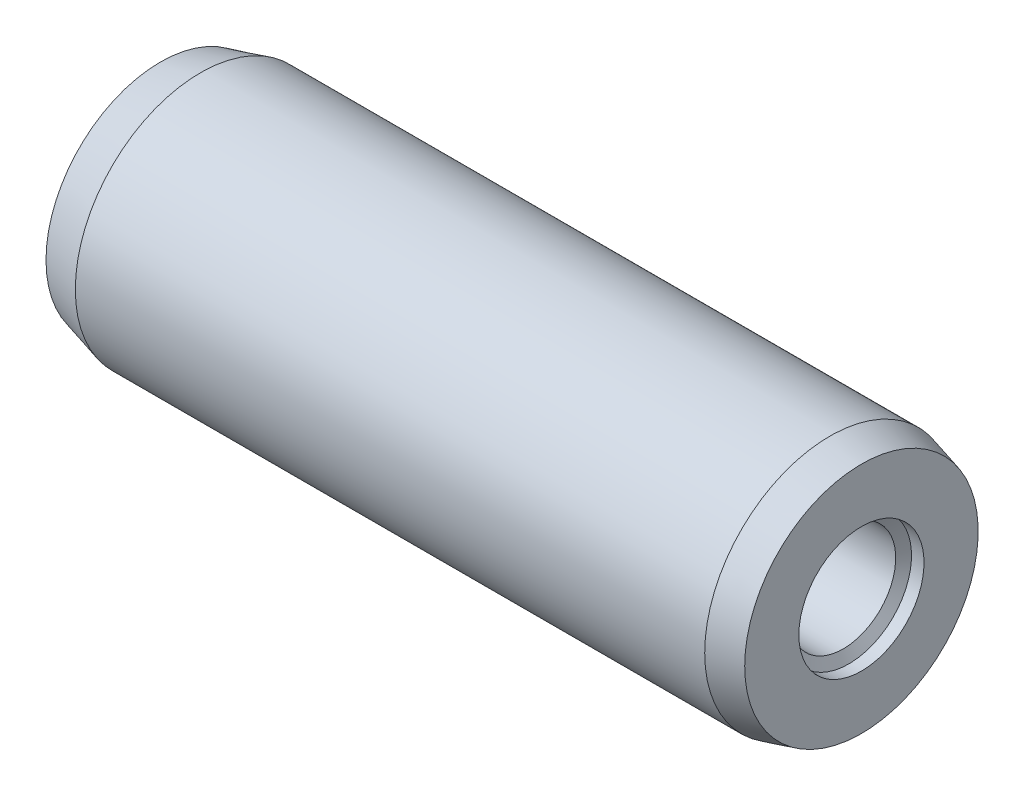
SolidWorks part; units mm, degrees
ref_plane "Plane1" through (0, 0, 0) normal (0, 0, 1) x (1, 0, 0)
ref_plane "Plane2" through (0, 0, 0) normal (0, 1, 0) x (1, 0, 0)
ref_plane "Plane3" through (0, 0, 0) normal (1, 0, 0) x (0, 0, -1)
sketch "Sketch1" plane through (0, 0, 0) normal (0, 0, 1) x (1, 0, 0)
  line L0 (-10, 0) -> (106, 0) construction
  line L1 (0, 0) -> (0, 22.8564)
  line L2 (8, 25) -> (133.7, 25)
  line L3 (140, 23.3119) -> (140, 12.5)
  line L4 (83.691, 0) -> (0, 0)
  line L5 (8, 25) -> (0, 22.8564)
  line L6 (140, 23.3119) -> (133.7, 25)
  line L7 (83.691, 0) -> (90, 10.5)
  line L8 (90, 10.5) -> (136.3453, 10.5)
  line L9 (136.3453, 10.5) -> (137.5, 12.5)
  line L10 (136.3453, -10.5) -> (137.5, -12.5) construction
  line L11 (137.5, 12.5) -> (140, 12.5)
  line L12 (83.691, 0) -> (90, -10.5) construction
  dimension "D1" = 15
  dimension "Length" = 140
  dimension "ChamferLength2" = 8
  dimension "D2" = 75
  dimension "ChamferLength1" = 6.3
  dimension "D3" = 120
  dimension "Diameter" = 50
  dimension "CboreDia" = 25
  dimension "D4" = 118
  dimension "CboreDepth" = 2.5
  dimension "TapDrillDepth" = 50
  dimension "TapDrillDia" = 21
revolve "Base-Revolve" add sketch "Sketch1" angle 360 about L0
cosmetic thread "Cosmetic Thread1" [suppressed] parameters "ThreadDepth"=36, "ThreadDia"=24
